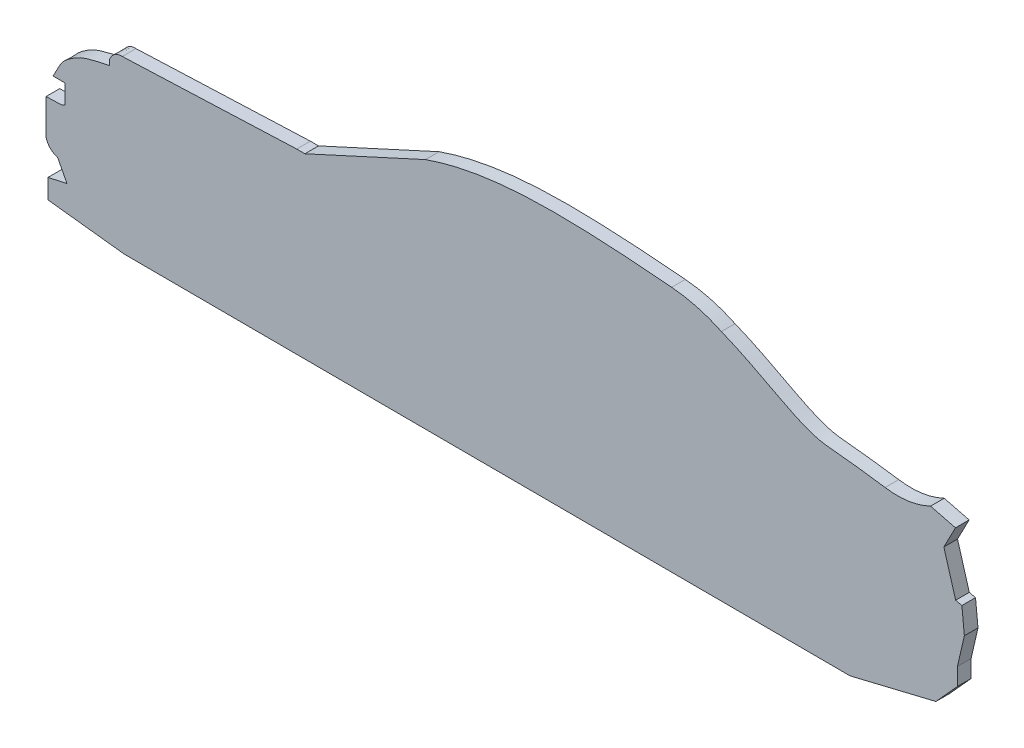
SolidWorks part; units mm, degrees
ref_plane "Front Plane" through (0, 0, 0) normal (0, 0, 1) x (1, 0, 0)
ref_plane "Top Plane" through (0, 0, 0) normal (0, 1, 0) x (1, 0, 0)
ref_plane "Right Plane" through (0, 0, 0) normal (1, 0, 0) x (0, 0, -1)
sketch "Sketch1" plane through (0, 0, 0) normal (0, 0, 1) x (1, 0, 0)
  line L42 (-126.9018, 63.4514) -> (-155.0026, 50.576)
  line L43 (-155.0026, 50.576) -> (-156.9151, 50.576)
  line L44 (-156.9151, 50.576) -> (-197.5327, 48.9336)
  line L45 (-200.4878, 46.8775) -> (-200.4878, 45.6192)
  line L46 (-213.6743, 36.9222) -> (-210.8773, 36.9222)
  line L47 (-210.8773, 36.9222) -> (-210.8773, 32.5408)
  line L48 (-215.312, 31.9693) -> (-215.312, 23.7712)
  line L49 (-212.6182, 21.0534) -> (-210.4133, 16.8527)
  line L50 (-210.4133, 16.8527) -> (-214.8427, 15.8907)
  line L51 (-214.8427, 15.8907) -> (-214.8427, 11.3375)
  line L52 (-214.8427, 11.3375) -> (-197.1028, 9.286)
  line L53 (-197.1028, 9.286) -> (-28.0092, 8.7395)
  line L54 (-28.0092, 8.7395) -> (-8.009, 13.5715)
  line L55 (-8.009, 13.5715) -> (-3.0001, 19.1104)
  line L56 (-3.0001, 19.1104) -> (-3.0001, 23.1503)
  line L57 (-3.0001, 23.1503) -> (-1.3855, 30.1459)
  line L58 (-1.3855, 30.1459) -> (-1.9631, 35.9655)
  line L59 (-1.9631, 35.9655) -> (-3.4103, 36.2995)
  line L60 (-3.4103, 36.2995) -> (-6.1596, 45.673)
  line L61 (-6.1596, 45.673) -> (-3.4515, 50.8915)
  line L62 (-3.4515, 50.8915) -> (-9.254, 52.3595)
  spline S16 degree 3 poles (-69.5734, 66.3508) (-70.7762, 66.4631) (-71.9801, 66.5608) (-74.3879, 66.7554) (-75.5916, 66.8546) (-79.2042, 67.1346) (-81.6149, 67.2898) (-86.4401, 67.5476) (-88.8534, 67.655) (-93.6817, 67.7954) (-96.0968, 67.8272) (-100.9298, 67.7743) (-103.3403, 67.6895) (-108.1344, 67.3654) (-110.5193, 67.126) (-115.259, 66.454) (-117.6138, 66.0215) (-121.1186, 65.1973) (-122.2823, 64.8933) (-124.5998, 64.2216) (-125.7532, 63.8521) (-126.9018, 63.4514) knots 0 0 0 0 0.0625 0.0625 0.125 0.125 0.25 0.25 0.375 0.375 0.5 0.5 0.625 0.625 0.75 0.75 0.875 0.875 0.9375 0.9375 1 1 1 1
  spline S17 degree 3 poles (-197.5327, 48.9336) (-197.8569, 48.9548) (-198.1757, 48.9195) (-198.7997, 48.7404) (-199.0893, 48.601) (-199.6192, 48.2271) (-199.8473, 48.0015) (-200.1308, 47.6056) (-200.2134, 47.4664) (-200.3543, 47.1737) (-200.42, 47.0251) (-200.4878, 46.8775) knots 0 0 0 0 0.25 0.25 0.5 0.5 0.75 0.75 0.875 0.875 1 1 1 1
  spline S18 degree 3 poles (-200.4878, 45.6192) (-201.1753, 45.5045) (-201.8557, 45.3585) (-202.8719, 45.1208) (-203.21, 45.0385) (-203.8858, 44.8728) (-204.224, 44.7909) (-205.236, 44.5344) (-205.9065, 44.3463) (-206.875, 43.9863) (-207.1918, 43.853) (-207.8118, 43.5563) (-208.4189, 43.2311) (-209.0053, 42.8601) (-209.5842, 42.4726) (-209.8694, 42.2734) (-210.694, 41.6435) (-211.2015, 41.178) (-211.7301, 40.4822) (-211.8311, 40.3365) (-212.0181, 40.0367) (-212.1016, 39.8813) (-212.681, 38.7911) (-213.1777, 37.8566) (-213.6743, 36.9222) knots 0 0 0 0 0.125 0.125 0.1875 0.1875 0.25 0.25 0.375 0.375 0.4375 0.4375 0.5 0.5625 0.5625 0.625 0.625 0.75 0.75 0.78125 0.78125 0.8125 0.8125 1 1 1 1
  spline S19 degree 3 poles (-210.8773, 32.5408) (-211.0196, 32.4093) (-211.1816, 32.3084) (-211.3982, 32.204) (-211.4425, 32.1845) (-211.5321, 32.153) (-211.5777, 32.1412) (-211.7156, 32.1116) (-211.809, 32.0995) (-212.0912, 32.073) (-212.2813, 32.0685) (-212.6604, 32.0634) (-212.85, 32.0634) (-213.229, 32.0575) (-213.4184, 32.0497) (-214.1758, 32.0175) (-214.7439, 31.9934) (-215.312, 31.9693) knots 0 0 0 0 0.125 0.125 0.15625 0.15625 0.1875 0.1875 0.25 0.25 0.375 0.375 0.5 0.5 0.625 0.625 1 1 1 1
  spline S20 degree 3 poles (-215.312, 23.7712) (-215.2527, 23.6141) (-215.1957, 23.4557) (-215.0691, 23.1454) (-214.9984, 22.9945) (-214.8401, 22.7022) (-214.7524, 22.5609) (-214.5572, 22.2897) (-214.4489, 22.1593) (-214.1022, 21.8004) (-213.8385, 21.6004) (-213.3989, 21.3535) (-213.2474, 21.2814) (-212.9376, 21.1555) (-212.7787, 21.1025) (-212.6182, 21.0534) knots 0 0 0 0 0.125 0.125 0.25 0.25 0.375 0.375 0.5 0.5 0.75 0.75 0.875 0.875 1 1 1 1
  spline S21 degree 3 poles (-9.254, 52.3595) (-9.6689, 52.1772) (-10.0823, 51.9908) (-10.9239, 51.6579) (-11.3508, 51.5077) (-12.2169, 51.2409) (-12.6567, 51.1242) (-13.541, 50.9271) (-13.9865, 50.8462) (-14.8837, 50.7197) (-15.3366, 50.674) (-16.2398, 50.6176) (-16.6909, 50.6067) (-18.0427, 50.6228) (-18.942, 50.6985) (-19.8397, 50.8319) knots 0 0 0 0 0.125 0.125 0.25 0.25 0.375 0.375 0.5 0.5 0.625 0.625 0.75 0.75 1 1 1 1
  spline S22 degree 3 poles (-19.8397, 50.8319) (-23.1964, 51.3616) (-26.5717, 51.739) (-30.3724, 52.1344) (-30.7947, 52.1779) (-31.6395, 52.2647) (-32.062, 52.3075) (-33.3263, 52.4471) (-34.1648, 52.5545) (-35.8062, 52.888) (-36.6045, 53.1293) (-38.1814, 53.6769) (-38.9588, 53.9877) (-41.2682, 54.9955) (-42.7786, 55.7679) (-45.7837, 57.3294) (-47.2812, 58.1206) (-51.7932, 60.4541) (-54.8281, 61.9547) (-57.9783, 63.2202) knots 0 0 0 0 0.25 0.25 0.28125 0.28125 0.3125 0.3125 0.375 0.375 0.4375 0.4375 0.5 0.5 0.625 0.625 0.75 0.75 1 1 1 1
  spline S23 degree 3 poles (-57.9783, 63.2202) (-59.7982, 64.0876) (-61.681, 64.7892) (-65.5731, 65.8414) (-67.564, 66.1855) (-69.5734, 66.3508) knots 0 0 0 0 0.5 0.5 1 1 1 1
extrude "Boss-Extrude1" add sketch "Sketch1" along normal blind 3.18
